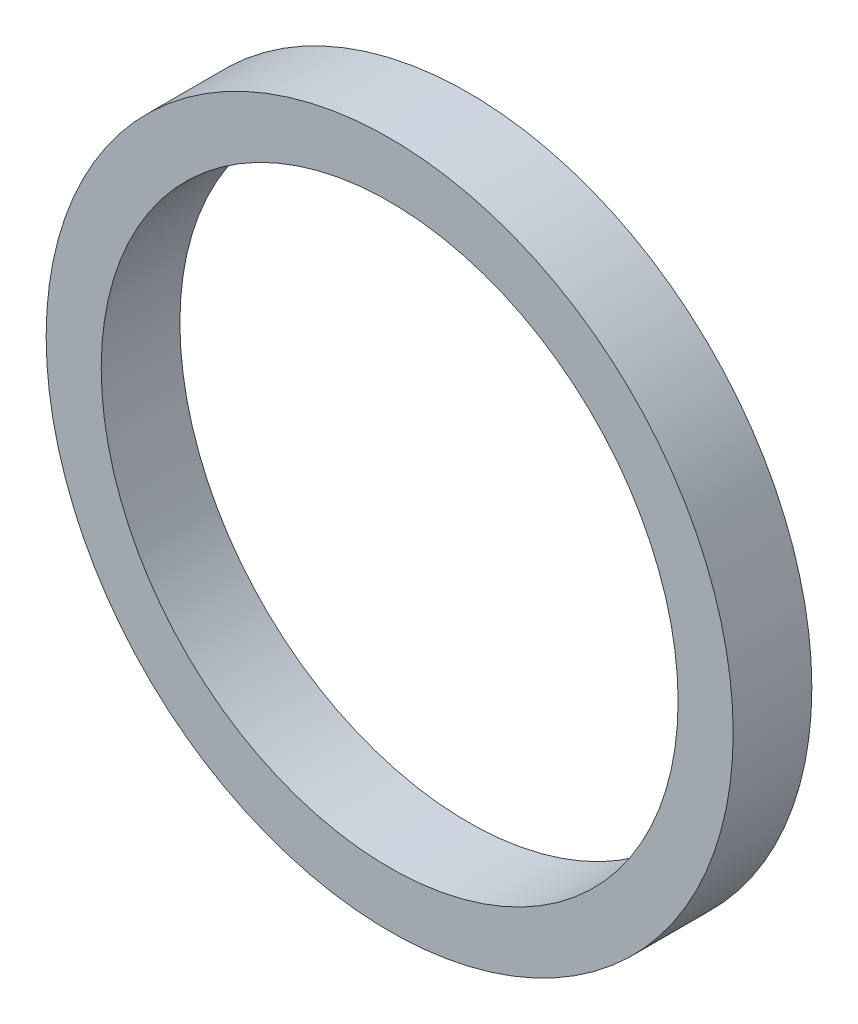
SolidWorks part; units mm, degrees
material "Gray Cast Iron"
ref_plane "Front Plane" through (0, 0, 0) normal (0, 0, 1) x (1, 0, 0)
ref_plane "Top Plane" through (0, 0, 0) normal (0, 1, 0) x (1, 0, 0)
ref_plane "Right Plane" through (0, 0, 0) normal (1, 0, 0) x (0, 0, -1)
sketch "Sketch1" plane through (0, 0, 0) normal (0, 0, 1) x (1, 0, 0)
  circle A0 centre (0, 0) radius 13.1
  circle A1 centre (0, 0) radius 11
  dimension "D1" = 26.2
  dimension "D2" = 22
extrude "Boss-Extrude1" add sketch "Sketch1" along normal mid plane 3 contours A0 A1
